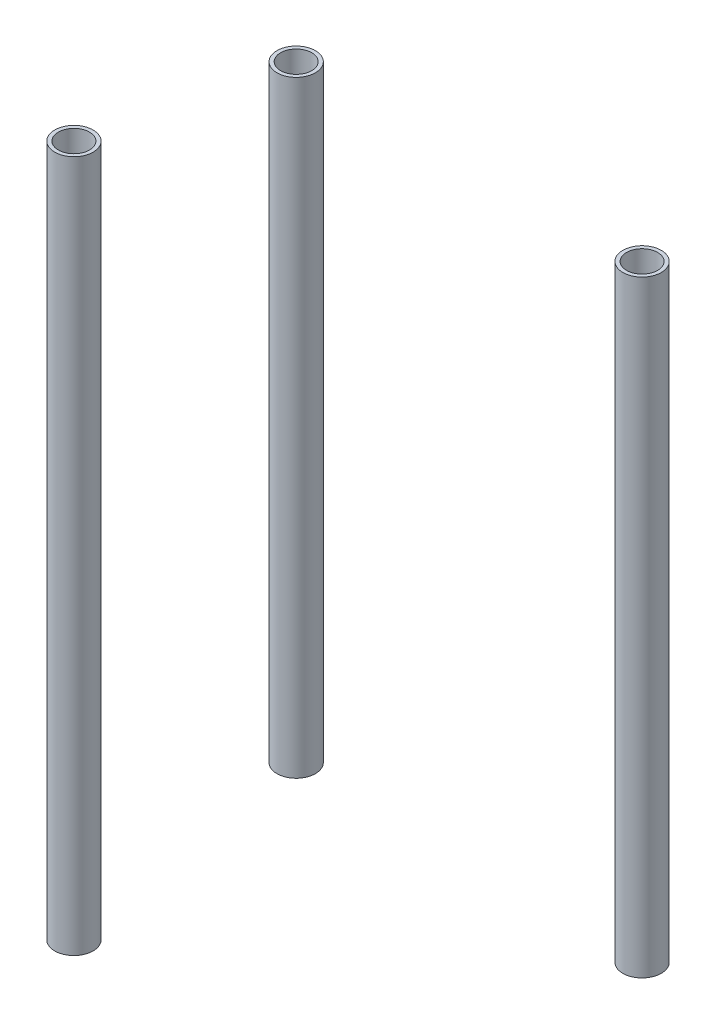
SolidWorks part; units mm, degrees
material "AISI 4130 Steel, annealed at 865C"
material "AISI 4130 Steel, annealed at 865C"
material "AISI 4130 Steel, annealed at 865C"
material "AISI 4130 Steel, annealed at 865C"
material "AISI 4130 Steel, annealed at 865C"
material "AISI 4130 Steel, annealed at 865C"
material "AISI 4130 Steel, annealed at 865C"
material "AISI 4130 Steel, annealed at 865C"
material "AISI 4130 Steel, annealed at 865C"
material "AISI 4130 Steel, annealed at 865C"
material "AISI 4130 Steel, annealed at 865C"
material "AISI 4130 Steel, annealed at 865C"
material "AISI 4130 Steel, annealed at 865C"
material "AISI 4130 Steel, annealed at 865C"
material "AISI 4130 Steel, annealed at 865C"
material "AISI 4130 Steel, annealed at 865C"
material "AISI 4130 Steel, annealed at 865C"
material "AISI 4130 Steel, annealed at 865C"
material "AISI 4130 Steel, annealed at 865C"
material "AISI 4130 Steel, annealed at 865C"
material "AISI 4130 Steel, annealed at 865C"
material "AISI 4130 Steel, annealed at 865C"
material "AISI 4130 Steel, annealed at 865C"
material "AISI 4130 Steel, annealed at 865C"
material "AISI 4130 Steel, annealed at 865C"
material "AISI 4130 Steel, annealed at 865C"
material "AISI 4130 Steel, annealed at 865C"
material "AISI 4130 Steel, annealed at 865C"
material "AISI 4130 Steel, annealed at 865C"
material "AISI 4130 Steel, annealed at 865C"
material "AISI 4130 Steel, annealed at 865C"
material "AISI 4130 Steel, annealed at 865C"
material "AISI 4130 Steel, annealed at 865C"
material "AISI 4130 Steel, annealed at 865C"
material "AISI 4130 Steel, annealed at 865C"
material "AISI 4130 Steel, annealed at 865C"
material "AISI 4130 Steel, annealed at 865C"
material "AISI 4130 Steel, annealed at 865C"
material "AISI 4130 Steel, annealed at 865C"
material "AISI 4130 Steel, annealed at 865C"
material "AISI 4130 Steel, annealed at 865C"
material "AISI 4130 Steel, annealed at 865C"
material "AISI 4130 Steel, annealed at 865C"
material "AISI 4130 Steel, annealed at 865C"
material "AISI 4130 Steel, annealed at 865C"
material "AISI 4130 Steel, annealed at 865C"
material "AISI 4130 Steel, annealed at 865C"
material "AISI 4130 Steel, annealed at 865C"
material "AISI 4130 Steel, annealed at 865C"
material "AISI 4130 Steel, annealed at 865C"
material "AISI 4130 Steel, annealed at 865C"
material "AISI 4130 Steel, annealed at 865C"
material "AISI 4130 Steel, annealed at 865C"
material "AISI 4130 Steel, annealed at 865C"
material "AISI 4130 Steel, annealed at 865C"
material "AISI 4130 Steel, annealed at 865C"
material "AISI 4130 Steel, annealed at 865C"
material "AISI 4130 Steel, annealed at 865C"
material "AISI 4130 Steel, annealed at 865C"
material "AISI 4130 Steel, annealed at 865C"
material "AISI 4130 Steel, annealed at 865C"
material "AISI 4130 Steel, annealed at 865C"
material "AISI 4130 Steel, annealed at 865C"
material "AISI 4130 Steel, annealed at 865C"
material "AISI 4130 Steel, annealed at 865C"
material "AISI 4130 Steel, annealed at 865C"
material "AISI 4130 Steel, annealed at 865C"
material "AISI 4130 Steel, annealed at 865C"
material "AISI 4130 Steel, annealed at 865C"
material "AISI 4130 Steel, annealed at 865C"
material "AISI 4130 Steel, annealed at 865C"
material "AISI 4130 Steel, annealed at 865C"
material "AISI 4130 Steel, annealed at 865C"
material "AISI 4130 Steel, annealed at 865C"
material "AISI 4130 Steel, annealed at 865C"
material "AISI 4130 Steel, annealed at 865C"
material "AISI 4130 Steel, annealed at 865C"
other "Markup1"
sketch "Sketch149" plane through (1625.6, 358.9875, 1104.9) normal (0.0564, 0.9911, 0.1203) x (-0.9627, 0.0859, -0.2567)
material "AISI 4130 Steel, annealed at 865C"
ref_plane "X-Y Datum" through (0, 0, 0) normal (0, 0, 1) x (1, 0, 0)
ref_plane "X-Z Datum" through (0, 0, 0) normal (0, 1, 0) x (1, 0, 0)
ref_plane "Y-Z Datum" through (0, 0, 0) normal (1, 0, 0) x (0, 0, -1)
ref_plane "floor plane" through (0, 0, 0) normal (0, 0, 1) x (1, 0, 0)
ref_plane "main hoop plane" through (0, 0, 0) normal (1, 0, 0) x (0, 0, -1)
ref_plane "centerline plane" through (0, 0, 0) normal (0, 1, 0) x (1, 0, 0)
sketch "Percy" plane through (0, 0, 0) normal (0, 1, 0) x (1, 0, 0)
  line L0 (91.269, -794.0031) -> (133.848, -517.2595)
  line L1 (133.848, -517.2595) -> (414.9005, -115.875)
  line L2 (-394.8863, 0) -> (394.8863, 0) construction
  line L3 (414.9005, -115.875) -> (1324.4394, -215.6946)
  line L4 (-136.5848, -12.7) -> (1428.0804, -12.7) construction
  line L5 (414.9005, -15.875) -> (625.4675, -15.875) construction
  circle A0 centre (91.269, -794.0031) radius 150
  circle A1 centre (133.848, -517.2595) radius 100
  circle A2 centre (414.9005, -115.875) radius 100
  dimension "D1" = 300
  dimension "D3" = 200
  dimension "D5" = 200
  dimension "D8" = 12.7
  dimension "D2" = 280
  dimension "D4" = 490
  dimension "D6" = 915
  dimension "D7" = 55
  dimension "D9" = 3.175
sketch "Profile Sketch" plane through (0, 0, 0) normal (0, 1, 0) x (1, 0, 0)
  line L1 (5.2716, -266.7) -> (844.5427, -266.7)
  line L2 (0, -954.9) -> (-696.7775, -162.56)
  line L3 (-696.7775, -162.56) -> (-468.1775, -162.56)
  line L4 (-468.1775, -162.56) -> (5.2716, -266.7)
  line L6 (0, -1104.9) -> (0, -294.5497)
  line L7 (20.3571, -242.7037) -> (292.8532, 50.8)
  line L9 (844.5427, -482.6) -> (844.5427, 0)
  line L10 (844.5427, 0) -> (292.8532, 50.8)
  line L11 (844.5427, 0) -> (844.5427, -527.05)
  line L12 (844.5427, -482.6) -> (1568.4427, -342.9)
  line L13 (358.071, 32.041) -> (22.8726, -464.911) construction
  line L14 (844.5427, 0) -> (1568.4427, 0)
  line L15 (1568.4427, 0) -> (1568.4427, -342.9)
  line L16 (1073.1427, -156.8069) -> (844.5427, -156.8069)
  line L17 (0, -1104.9) -> (844.5427, -527.05) construction
  line L18 (0, -1104.9) -> (-696.7775, -162.56) construction
  line L19 (207.056, -963.2289) -> (175.9721, -917.7989) construction
  line L20 (175.9721, -917.7989) -> (333.5373, -809.9901) construction
  line L22 (-678.2927, 126.0856) -> (1356.9996, 126.0856)
  line L23 (-696.7775, -15.6718) -> (-468.1775, -15.6718)
  line L24 (292.8532, 50.8) -> (-265.9468, 50.8)
  line L25 (-696.7775, -15.6718) -> (-696.7775, -162.56)
  line L26 (844.5427, -266.7) -> (1073.1427, -156.8069)
  line L27 (358.071, 32.041) -> (771.3682, -6.0158) construction
  line L29 (1073.1427, -156.8069) -> (1073.1427, 0)
  line L30 (1073.1427, -156.8069) -> (1568.4427, -342.9)
  line L31 (1073.1427, -156.8069) -> (1568.4427, 0)
  line L32 (844.5427, 0) -> (1073.1427, -156.8069)
  line L33 (292.8532, 50.8) -> (844.5427, -266.7)
  line L34 (-265.9468, 50.8) -> (-468.1775, -15.6718)
  line L35 (-116.3625, -947.5283) -> (-29.3412, -883.1837) construction
  line L36 (-29.3412, -883.1837) -> (-74.2119, -822.4994) construction
  line L37 (-468.1775, -162.56) -> (-468.1775, -15.6718)
  line L38 (-265.9468, 50.8) -> (5.2716, -266.7)
  circle A0 centre (91.269, -794.0031) radius 150 construction
  arc A2 (20.3571, -242.7037) -> (0, -294.5497) centre (76.2, -294.5497) ccw
  point P2 (-582.4775, -162.56)
  point P3 (958.8427, -156.8069)
  point P12 (292.8532, 50.8)
  point P38 (186.0655, 0)
  dimension "D5" = 1104.9
  dimension "D17" = 76.2
  dimension "D2" = 150
  dimension "D3" = 55.0463
  dimension "D4" = 108.2263
  dimension "D6" = 288.6456
  dimension "D7" = 342.9
  dimension "D8" = 527.05
  dimension "D9" = 482.6
  dimension "D10" = 282.8925
  dimension "D11" = 654.243
  dimension "D12" = 658.4772
  dimension "D13" = 723.9
  dimension "D14" = 882.843
  dimension "D15" = 2265.2203
  dimension "D16" = 887.0772
  dimension "D18" = 266.7
  dimension "D19" = 12.7
  dimension "D20" = 558.8
  dimension "D21" = 50.8
  dimension "D22" = 126.0856
  dimension "D23" = 141.7574
  dimension "D24" = 56
  dimension "D25" = 1541.3203
sketch "Accumulator" plane through (0, 0, 0) normal (0, 1, 0) x (1, 0, 0)
  line L4 (-262.0664, 39.0031) -> (271.3336, 39.0031)
  line L5 (271.3336, 39.0031) -> (271.3336, -138.7969)
  line L6 (271.3336, -138.7969) -> (-262.0664, -138.7969)
  line L7 (-262.0664, -138.7969) -> (-262.0664, 39.0031)
  dimension "D1" = 533.4
  dimension "D2" = 177.8
ref_plane "front bulkhead plane" through (1568.4427, 0, 0) normal (-1, 0, 0) x (0, 0, 1)
ref_plane "front suspension plane" through (1073.1427, 0, 0) normal (1, 0, 0) x (0, 0, -1)
ref_plane "front hoop plane" through (844.5427, 0, 0) normal (1, 0, 0) x (0, 0, -1)
ref_plane "rear suspension plane" through (-468.1775, 0, 0) normal (1, 0, 0) x (0, 0, -1)
ref_plane "rear bulkhead plane" through (-696.7775, 0, 0) normal (-1, 0, 0) x (0, 0, 1)
sketch "front bulkhead sketch" plane through (1568.4427, 0, 0) normal (-1, 0, 0) x (0, 0, 1)
  line L0 (342.9, -146.05) -> (342.9, 146.05)
  line L1 (342.9, 146.05) -> (0, 146.05)
  line L2 (0, 146.05) -> (0, -146.05)
  line L3 (342.9, 0) -> (0, 0) construction
  line L4 (342.9, -146.05) -> (0, -146.05)
  line L5 (342.9, 146.05) -> (0, -146.05)
  dimension "D1" = 292.1
  dimension "D2" = 342.9
sketch "front suspension sketch" plane through (1073.1427, 0, 0) normal (1, 0, 0) x (0, 0, -1)
  line L0 (0, -160.528) -> (0, 160.528)
  line L2 (0, 160.528) -> (-156.8069, 233.68)
  line L4 (0, 0) -> (-156.8069, 0) construction
  line L5 (-15.875, 0) -> (-215.875, 0) construction
  line L6 (0, -160.528) -> (-156.8069, -233.68)
  dimension "D1" = 160.528
  dimension "D2" = 233.68
sketch "front hoop sketch" plane through (844.5427, 0, 0) normal (1, 0, 0) x (0, 0, -1)
  line L0 (-502.0992, 151.8159) -> (-524.6242, 27.0833)
  line L1 (-517.2595, 0) -> (-115.875, 0) construction
  line L3 (-417.2595, 0) -> (-617.2595, 0) construction
  line L5 (-482.6, -326.7905) -> (-482.6, 326.7905) construction
  line L6 (0, 394.8863) -> (0, -394.8863) construction
  line L7 (0, -160.528) -> (0, 160.528)
  line L8 (-527.05, 0) -> (0, 0) construction
  line L10 (-502.0992, -151.8159) -> (-524.6242, -27.0833)
  line L14 (55, 0) -> (-55, 0) construction
  line L15 (0, -160.528) -> (-148.0936, -230.2172)
  line L16 (-165.8796, -236.0464) -> (-250.3026, -252.5965)
  line L17 (-502.0992, 151.8159) -> (-524.6242, 27.0833)
  line L18 (0, 160.528) -> (-148.0936, 230.2172)
  line L19 (-283.0163, -251.85) -> (-445.1667, -212.3044)
  line L20 (-283.0163, 251.85) -> (-445.1667, 212.3044)
  line L21 (-165.8796, 236.0464) -> (-250.3026, 252.5965)
  arc A0 (-524.6242, 27.0833) -> (-524.6242, -27.0833) centre (-374.65, 0) ccw
  arc A2 (-445.1667, -212.3044) -> (-502.0992, -151.8159) centre (-427.1121, -138.2742) cw
  arc A3 (-445.1667, 212.3044) -> (-502.0992, 151.8159) centre (-427.1121, 138.2742) ccw
  arc A4 (-148.0936, -230.2172) -> (-165.8796, -236.0464) centre (-180.5386, -161.2697) cw
  arc A5 (-148.0936, 230.2172) -> (-165.8796, 236.0464) centre (-180.5386, 161.2697) ccw
  arc A6 (-250.3026, -252.5965) -> (-283.0163, -251.85) centre (-264.9617, -177.8198) cw
  arc A7 (-250.3026, 252.5965) -> (-283.0163, 251.85) centre (-264.9617, 177.8198) ccw
  point P4 (-482.6, 190.5)
  point P5 (-482.6, -190.5)
  point P17 (-482.6, 0)
  point P27 (0, 0)
  point P30 (-156.8069, 233.68)
  point P36 (-527.05, 0)
  point P41 (-156.8069, -233.68)
  point P51 (-266.7, -254)
  point P55 (-266.7, 254)
  dimension "D2" = 152.4
  dimension "D3" = 76.2
  dimension "D1" = 233.68
  dimension "D4" = 76.2
  dimension "D7" = 76.2
  dimension "D5" = 160.528
  dimension "D6" = 381
  dimension "D8" = 44.45
  dimension "D9" = 508
sketch3d "main roll hoop sketch"
  line L0 (22.2475, -370.332, 239.8822) -> (292.8532, -370.332, -50.8)
  line L1 (22.2475, 370.332, 239.8822) -> (292.8532, 370.332, -50.8)
  line L2 (0, 0, 1104.9) -> (0, 0, 294.5497) construction
  line L3 (0, -95.7462, 1037.2887) -> (0, -359.4092, 294.5497)
  line L4 (0, 95.7462, 1037.2887) -> (0, 359.4092, 294.5497)
  line L5 (292.8532, -370.332, -50.8) -> (292.8532, 370.332, -50.8)
  arc A0 (0, -95.7462, 1037.2887) -> (0, 95.7462, 1037.2887) centre (0, 0, 1003.3) cw
  arc A1 (0, -359.4092, 294.5497) -> (22.2475, -370.332, 239.8822) centre (71.7104, -335.1246, 285.9289) ccw
  arc A2 (22.2475, 370.332, 239.8822) -> (0, 359.4092, 294.5497) centre (71.7104, 335.1246, 285.9289) cw
  point P2 (-101.6, 0, 1003.3)
  point P5 (97.4798, -402.7033, 309.9185)
  point P23 (97.4798, 402.7033, 309.9185)
  dimension "D1" = 101.6
  dimension "D3" = 740.664
  dimension "D4" = 76.2
  dimension "D2" = 740.664
sketch "rear suspension plane sketch" plane through (-468.1775, 0, 0) normal (1, 0, 0) x (0, 0, -1)
  line L0 (-15.6718, -200.5838) -> (-15.6718, 200.5838)
  line L2 (-162.56, -358.9875) -> (-162.56, 358.9875) construction
  line L3 (-15.6718, 200.5838) -> (-162.56, 228.6)
  line L5 (-162.56, 0) -> (-15.6718, 0) construction
  line L6 (-15.6718, -200.5838) -> (-162.56, -228.6)
  dimension "D1" = 200.5838
  dimension "D2" = 228.6
sketch "rear bulkhead sketch" plane through (-696.7775, 0, 0) normal (-1, 0, 0) x (0, 0, 1)
  line L0 (162.56, -228.6) -> (162.56, 228.6)
  line L1 (162.56, 228.6) -> (15.6718, 200.5838)
  line L2 (15.6718, 200.5838) -> (15.6718, -200.5838)
  line L3 (162.56, 0) -> (9.6507, 0) construction
  line L4 (162.56, -228.6) -> (15.6718, -200.5838)
  line L5 (215.875, 0) -> (15.875, 0) construction
  line L6 (162.56, 228.6) -> (15.6718, 0)
  line L7 (15.6718, 0) -> (162.56, -228.6)
  point P8 (15.6718, 0)
  dimension "D1" = 200.5838
  dimension "D2" = 228.6
sketch3d "Connecting Members"
  line L1 (844.5427, -326.7905, 482.6) -> (844.5427, 326.7905, 482.6) construction
  line L3 (1073.1427, 233.68, 156.8069) -> (1568.4427, 146.05, 342.9)
  line L4 (1073.1427, 233.68, 156.8069) -> (1568.4427, 146.05, 0)
  line L5 (1073.1427, -233.68, 156.8069) -> (844.5427, -254, 266.7)
  line L6 (1073.1427, 233.68, 156.8069) -> (844.5427, 160.528, 0)
  line L10 (844.5427, -254, 266.7) -> (5.3462, -367.2569, 266.7)
  line L12 (-468.1775, -228.6, 162.56) -> (5.3462, -367.2569, 266.7)
  line L13 (1568.4427, 146.05, 0) -> (1073.1427, 160.528, 0)
  line L19 (-468.1775, 228.6, 162.56) -> (-696.7775, 228.6, 162.56)
  line L20 (1073.1427, 160.528, 0) -> (844.5427, 160.528, 0)
  line L23 (292.8532, -370.332, -50.8) -> (844.5427, -254, 266.7)
  line L24 (-468.1775, -228.6, 162.56) -> (-696.7775, -228.6, 162.56)
  line L29 (-468.1775, 200.5838, 15.6718) -> (-696.7775, 200.5838, 15.6718)
  line L32 (292.8532, -370.332, -50.8) -> (844.5427, -160.528, 0)
  line L35 (1568.4427, 146.05, 342.9) -> (844.5427, 190.5, 482.6)
  line L39 (844.5427, -160.528, 0) -> (1073.1427, -233.68, 156.8069)
  line L41 (1073.1427, -233.68, 156.8069) -> (1568.4427, -146.05, 0)
  line L43 (1568.4427, -146.05, 342.9) -> (844.5427, -190.5, 482.6)
  line L45 (1073.1427, -233.68, 156.8069) -> (1568.4427, -146.05, 342.9)
  line L47 (-696.7775, -228.6, 162.56) -> (0, -124.9931, 954.9)
  line L48 (0, -95.7462, 1037.2887) -> (0, -359.4092, 294.5497) construction
  line L49 (-696.7775, 228.6, 162.56) -> (0, 124.9931, 954.9)
  line L57 (-468.1775, 228.6, 162.56) -> (-582.4775, 200.5838, 15.6718)
  line L58 (-582.4775, 200.5838, 15.6718) -> (-696.7775, 228.6, 162.56)
  line L59 (1568.4427, -146.05, 0) -> (1073.1427, -160.528, 0)
  line L65 (-265.9468, 370.332, -50.8) -> (292.8532, 370.332, -50.8)
  line L66 (5.3462, -367.2569, 266.7) -> (-265.9468, -370.332, -50.8)
  line L70 (1073.1427, -160.528, 0) -> (844.5427, -160.528, 0)
  line L75 (-468.1775, -200.5838, 15.6718) -> (-696.7775, -200.5838, 15.6718)
  line L76 (-468.1775, -228.6, 162.56) -> (-582.4775, -200.5838, 15.6718)
  line L77 (-582.4775, -200.5838, 15.6718) -> (-696.7775, -228.6, 162.56)
  line L78 (844.5427, 233.68, 156.8069) -> (1073.1427, 233.68, 156.8069)
  line L79 (1073.1427, -233.68, 156.8069) -> (844.5427, -233.68, 156.8069)
  line L81 (292.8532, 370.332, -50.8) -> (844.5427, 160.528, 0)
  line L85 (844.5427, 254, 266.7) -> (1073.1427, 233.68, 156.8069)
  line L89 (-265.9468, -370.332, -50.8) -> (292.8532, -370.332, -50.8)
  line L90 (-468.1775, -200.5838, 15.6718) -> (-265.9468, -370.332, -50.8)
  line L91 (-468.1775, -228.6, 162.56) -> (-265.9468, -370.332, -50.8)
  line L92 (292.8532, 370.332, -50.8) -> (844.5427, 254, 266.7)
  line L96 (844.5427, 254, 266.7) -> (5.3462, 367.2569, 266.7)
  line L97 (-468.1775, 228.6, 162.56) -> (-265.9468, 370.332, -50.8)
  line L98 (-468.1775, 200.5838, 15.6718) -> (-265.9468, 370.332, -50.8)
  line L99 (-468.1775, 228.6, 162.56) -> (5.3462, 367.2569, 266.7)
  line L100 (-468.1775, 228.6, 162.56) -> (-265.9468, 370.332, -50.8)
  line L101 (5.3462, 367.2569, 266.7) -> (-265.9468, 370.332, -50.8)
  line L102 (0, 124.9931, 954.9) -> (0, -124.9931, 954.9) construction
  line L103 (844.5427, -190.5, 482.6) -> (5.3462, -367.2569, 266.7)
  line L104 (5.3462, 367.2569, 266.7) -> (844.5427, 190.5, 482.6)
  line L105 (0, -247.5703, 609.6) -> (0, 247.5703, 609.6)
  line L106 (-265.9468, -370.332, -50.8) -> (-265.9468, 370.332, -50.8)
  line L108 (0, 95.7462, 1037.2887) -> (0, 359.4092, 294.5497) construction
  arc A0 (844.5427, 230.2172, 148.0936) -> (844.5427, 236.0464, 165.8796) centre (844.5427, 161.2697, 180.5386) ccw construction
  arc A2 (0, -359.4092, 294.5497) -> (22.2475, -370.332, 239.8822) centre (71.7104, -335.1246, 285.9289) ccw construction
  arc A4 (844.5427, -252.5965, 250.3026) -> (844.5427, -251.85, 283.0163) centre (844.5427, -177.8198, 264.9617) ccw construction
  point P22 (97.4798, -402.7033, 309.9185)
  point P26 (0, 0, 609.6)
  point P45 (768.3427, -177.8198, 264.9617)
  point P62 (920.7427, 161.2697, 180.5386)
  point P116 (844.5427, 233.68, 156.8069)
  dimension "D1" = 609.6
sketch "cockpit opening template" plane through (0, 0, 0) normal (0, 0, 1) x (1, 0, 0)
  line L0 (654.8407, -200) -> (654.8407, 200)
  line L1 (414.9005, 0) -> (1324.4394, 0) construction
  line L2 (654.8407, 200) -> (154.8407, 275)
  line L3 (154.8407, 275) -> (54.8407, 175)
  line L4 (54.8407, 175) -> (54.8407, -175)
  line L5 (241.269, 0) -> (-58.731, 0) construction
  line L6 (712.1619, 0) -> (-712.1619, 0) construction
  line L7 (154.8407, -275) -> (54.8407, -175)
  line L8 (654.8407, -200) -> (154.8407, -275)
  point P0 (54.8407, 0)
  point P20 (654.8407, 0)
  dimension "D1" = 200
  dimension "D2" = 75
  dimension "D3" = 100
  dimension "D4" = 100
  dimension "D5" = 600
  dimension "D6" = 175
ref_plane "cross section template plane" through (1324.4394, 0, 0) normal (1, 0, 0) x (0, 0, -1)
sketch "cross section template" plane through (1324.4394, 0, 0) normal (1, 0, 0) x (0, 0, -1)
  line L1 (0, 146.05) -> (0, -146.05) construction
  line L2 (0, 125) -> (-50, 175)
  line L3 (-50, 175) -> (-300, 175)
  line L4 (-300, 175) -> (-350, 125)
  line L5 (-350, 125) -> (-350, 50)
  line L6 (-517.2595, 0) -> (-115.875, 0) construction
  line L7 (-350, 0) -> (0, 0) construction
  line L8 (-300, -175) -> (-350, -125)
  line L9 (-50, -175) -> (-300, -175)
  line L10 (0, -125) -> (-50, -175)
  line L11 (-350, -50) -> (-350, -125)
  line L13 (0, 50) -> (0, 125)
  line L14 (0, -50) -> (0, -125)
  arc A0 (-350, -50) -> (-350, 50) centre (-350, 0) ccw
  arc A2 (0, 50) -> (0, -50) centre (0, 0) ccw
  dimension "D7" = 50
  dimension "D8" = 50
  dimension "D1" = 350
  dimension "D2" = 175
  dimension "D3" = 50
  dimension "D4" = 50
  dimension "D5" = 50
  dimension "D6" = 50
other "front bulkhead 1.00 X 0.065IN"
ref_plane "Plane1" [suppressed] through (1568.4427, -146.05, 342.9) normal (0, 1, 0) x (0, 0, -1)
sketch "Sketch11" [suppressed] plane through (1568.4427, -146.05, 342.9) normal (0, 1, 0) x (0, 0, -1)
  circle A0 centre (0, 0) radius 12.7
  circle A1 centre (0, 0) radius 11.049
  point P4 (0, 0)
  dimension "D1" = 25.4
  dimension "D2" = 1.651
other "front bulkhead diagonal 1.00 X 0.049IN(1)"
ref_plane "Plane2" [suppressed] through (1568.4427, 146.05, 342.9) normal (0, -0.6485, -0.7612) x (0, -0.7612, 0.6485)
sketch "Sketch13" [suppressed] plane through (1568.4427, 146.05, 342.9) normal (0, -0.6485, -0.7612) x (0, -0.7612, 0.6485)
  circle A0 centre (0, 0) radius 12.7
  circle A1 centre (0, 0) radius 11.4554
  point P4 (0, 0)
  dimension "D1" = 25.4
  dimension "D2" = 1.2446
other "front connecting tubes (incl fbh support) 1.00 X 0.049IN(4)"
ref_plane "Plane6" [suppressed] through (844.5427, 254, 266.7) normal (0.8984, -0.0799, -0.4319) x (-0.4207, 0.1263, -0.8984)
sketch "Sketch152" [suppressed] plane through (844.5427, 254, 266.7) normal (0.8984, -0.0799, -0.4319) x (-0.4207, 0.1263, -0.8984)
  circle A0 centre (0, 0) radius 12.7
  circle A1 centre (0, 0) radius 11.4554
  point P4 (0, 0)
  dimension "D1" = 25.4
  dimension "D2" = 1.2446
other "front hoop 1.00 X 0.095IN(1)"
ref_plane "Plane7" [suppressed] through (844.5427, 160.528, 0) normal (0, 0.4258, 0.9048) x (0, -0.9048, 0.4258)
sketch "Sketch141" [suppressed] plane through (844.5427, 160.528, 0) normal (0, 0.4258, 0.9048) x (0, -0.9048, 0.4258)
  circle A0 centre (0, 0) radius 12.7
  circle A1 centre (0, 0) radius 10.287
  point P4 (0, 0)
  dimension "D1" = 25.4
  dimension "D2" = 2.413
other "forward front hoop bracing 1.00 X 0.065IN(2)"
ref_plane "Plane12" [suppressed] through (1568.4427, 146.05, 342.9) normal (-0.9801, 0.0602, 0.1891) x (0.1922, 0.0496, 0.9801)
sketch "Sketch157" [suppressed] plane through (1568.4427, 146.05, 342.9) normal (-0.9801, 0.0602, 0.1891) x (0.1922, 0.0496, 0.9801)
  circle A0 centre (0, 0) radius 12.7
  circle A1 centre (0, 0) radius 11.049
  point P4 (0, 0)
  dimension "D1" = 25.4
  dimension "D2" = 1.651
other "Trim/Extend14" [suppressed]
other "Trim/Extend18" [suppressed]
other "Trim/Extend34" [suppressed]
other "Trim/Extend32" [suppressed]
other "side impact structure 1.00 X 0.065IN(5)"
ref_plane "Plane20" [suppressed] through (844.5427, -254, 266.7) normal (-0.991, -0.1337, 0) x (0.0179, -0.1325, 0.991)
sketch "Sketch165" [suppressed] plane through (844.5427, -254, 266.7) normal (-0.991, -0.1337, 0) x (0.0179, -0.1325, 0.991)
  circle A0 centre (0, 0) radius 12.7
  circle A1 centre (0, 0) radius 11.049
  point P4 (0, 0)
  dimension "D1" = 25.4
  dimension "D2" = 1.651
other "rear front hoop bracing 0.50 X 0.049IN(1)"
ref_plane "Plane11" [suppressed] through (5.3462, 367.2569, 266.7) normal (0.9489, -0.1999, 0.2441) x (0.2762, 0.1524, -0.9489)
sketch "Sketch158" [suppressed] plane through (5.3462, 367.2569, 266.7) normal (0.9489, -0.1999, 0.2441) x (0.2762, 0.1524, -0.9489)
  circle A0 centre (0, 0) radius 6.35
  circle A1 centre (0, 0) radius 5.1054
  point P4 (0, 0)
  dimension "D1" = 12.7
  dimension "D2" = 1.2446
other "main roll hoop 1.00 X 0.095IN(2)"
ref_plane "Plane22" through (22.2475, -370.332, 239.8822) normal (0.6814, 0, -0.7319) x (-0.7319, 0, -0.6814)
sketch "Sketch169" plane through (22.2475, -370.332, 239.8822) normal (0.6814, 0, -0.7319) x (-0.7319, 0, -0.6814)
  circle A0 centre (0, 0) radius 12.7
  circle A1 centre (0, 0) radius 10.287
  point P4 (0, 0)
  dimension "D1" = 25.4
  dimension "D2" = 2.413
other "shoulder haness mounting bar 1.00 X 0.095IN(1)"
ref_plane "Plane21" through (0, -247.5703, 609.6) normal (0, 1, 0) x (1, 0, 0)
sketch "Sketch168" plane through (0, -247.5703, 609.6) normal (0, 1, 0) x (1, 0, 0)
  circle A0 centre (0, 0) radius 12.7
  circle A1 centre (0, 0) radius 10.287
  point P4 (0, 0)
  dimension "D1" = 25.4
  dimension "D2" = 2.413
other "main hoop bracing 1.00 X 0.065IN(5)"
ref_plane "Plane15" through (-696.7775, -228.6, 162.56) normal (0.6572, 0.0977, 0.7473) x (0.7528, -0.0368, -0.6572)
sketch "Sketch134" plane through (-696.7775, -228.6, 162.56) normal (0.6572, 0.0977, 0.7473) x (0.7528, -0.0368, -0.6572)
  circle A0 centre (0, 0) radius 12.7
  circle A1 centre (0, 0) radius 11.049
  point P4 (0, 0)
  dimension "D1" = 25.4
  dimension "D2" = 1.651
other "other rear structural tubing 1.00 X 0.049IN(1)"
ref_plane "Plane23" through (-696.7775, -228.6, 162.56) normal (0, 1, 0) x (0, 0, -1)
sketch "Sketch173" plane through (-696.7775, -228.6, 162.56) normal (0, 1, 0) x (0, 0, -1)
  circle A0 centre (0, 0) radius 10.287
  circle A1 centre (0, 0) radius 12.7
  point P3 (0, 0)
  dimension "In_dia" = 20.574
  dimension "Out_dia" = 25.4
other "Round_tubing 1.00 X 0.065IN(4)"
ref_plane "Plane18" [suppressed] through (1568.4427, -146.05, 0) normal (-0.9996, -0.0292, 0) x (0.0009, -0.0292, 0.9996)
sketch "Sketch1" [suppressed] plane through (1568.4427, -146.05, 0) normal (-0.9996, -0.0292, 0) x (0.0009, -0.0292, 0.9996)
  circle A0 centre (0, 0) radius 12.7
  circle A1 centre (0, 0) radius 11.049
  point P4 (0, 0)
  dimension "D1" = 25.4
  dimension "D2" = 1.651
other "Trim/Extend40" [suppressed]
other "Trim/Extend41" [suppressed]
other "Trim/Extend42" [suppressed]
other "Trim/Extend43" [suppressed]
